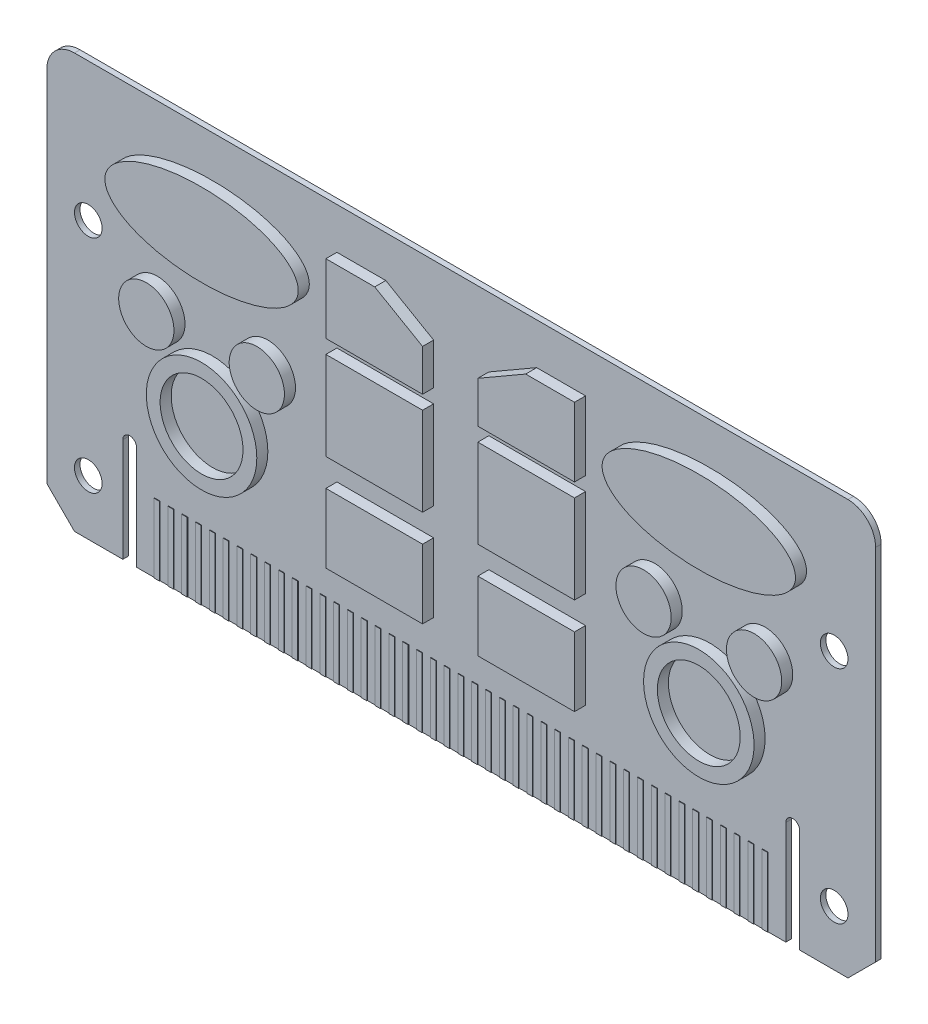
SolidWorks part; units mm, degrees
ref_plane "Front Plane" through (0, 0, 0) normal (0, 0, 1) x (1, 0, 0)
ref_plane "Top Plane" through (0, 0, 0) normal (0, 1, 0) x (1, 0, 0)
ref_plane "Right Plane" through (0, 0, 0) normal (1, 0, 0) x (0, 0, -1)
sketch "Sketch1" plane through (0, 0, 0) normal (0, 0, 1) x (1, 0, 0)
  line L0 (-300, 150) -> (-300, 0)
  line L1 (-300, 0) -> (0, 0)
  line L2 (0, 0) -> (0, 150)
  line L3 (0, 150) -> (-300, 150)
  point P4 (0, 0)
  point P5 (0, 0)
  point P6 (-125.1878, -83.3597)
  point P7 (-117.2815, -83.3597)
  point P8 (29.0712, -106.5204)
  point P9 (-94.6638, 45.4314)
  dimension "D1" = 300
  dimension "D2" = 150
extrude "PCB Base" add sketch "Sketch1" along normal mid plane 2 contours L3 L0 L1 L2
sketch "Sketch2" plane through (0, 0, 1) normal (0, 0, 1) x (1, 0, 0)
  line L0 (-300, 0) -> (0, 0) construction
  line L1 (-300, 150) -> (-300, 0) construction
  line L2 (0, 0) -> (0, 150) construction
  line L7 (-195, 38) -> (-160, 38)
  line L8 (-195, 38) -> (-195, 63)
  line L13 (-195, 63) -> (-160, 63)
  line L14 (-160, 38) -> (-160, 63)
  line L15 (-195, 73) -> (-160, 73)
  line L16 (-195, 73) -> (-195, 105)
  line L17 (-195, 105) -> (-160, 105)
  line L18 (-160, 73) -> (-160, 105)
  line L19 (-195, 110) -> (-160, 110)
  line L20 (-195, 110) -> (-195, 135)
  line L21 (-195, 135) -> (-177.3205, 135)
  line L22 (-160, 110) -> (-160, 125)
  line L23 (-160, 125) -> (-177.3205, 135)
  line L24 (-150, 150) -> (-150, 0) construction
  line L25 (0, 150) -> (-300, 150) construction
  line L26 (-140, 125) -> (-122.6795, 135)
  line L27 (-140, 110) -> (-140, 125)
  line L28 (-105, 135) -> (-122.6795, 135)
  line L29 (-105, 110) -> (-105, 135)
  line L30 (-105, 110) -> (-140, 110)
  line L31 (-140, 73) -> (-140, 105)
  line L32 (-105, 105) -> (-140, 105)
  line L33 (-105, 73) -> (-105, 105)
  line L34 (-105, 73) -> (-140, 73)
  line L35 (-140, 38) -> (-140, 63)
  line L36 (-105, 63) -> (-140, 63)
  line L37 (-105, 38) -> (-105, 63)
  line L38 (-105, 38) -> (-140, 38)
  circle A0 centre (-260, 85) radius 10
  circle A1 centre (-220, 85) radius 10
  circle A2 centre (-240, 60) radius 15
  circle A3 centre (-240, 60) radius 20
  circle A4 centre (-60, 60) radius 20
  circle A5 centre (-60, 60) radius 15
  circle A6 centre (-80, 85) radius 10
  circle A7 centre (-40, 85) radius 10
  ellipse E0 centre (-240, 120) end of major axis (-275, 120) minor radius 15
  ellipse E1 centre (-60, 120) end of major axis (-25, 120) minor radius 15
  dimension "D1" = 20
  dimension "D5" = 30
  dimension "D8" = 5
  dimension "D2" = 85
  dimension "D3" = 40
  dimension "D4" = 40
  dimension "D6" = 60
  dimension "D7" = 60
  dimension "D9" = 60
  dimension "D10" = 120
  dimension "D11" = 70
  dimension "D12" = 30
  dimension "D13" = 38
  dimension "D14" = 73
  dimension "D15" = 25
  dimension "D16" = 32
  dimension "D17" = 110
  dimension "D18" = 135
  dimension "D19" = 160
  dimension "D20" = 195
  dimension "D21" = 125
  dimension "D22" = 120
extrude "Chips" add sketch "Sketch2" along normal blind 4
mirror "Mirror1" about plane through (0, 0, 0) normal (0, 0, 1) of "Chips"
sketch "Sketch3" plane through (0, 0, 1) normal (0, 0, 1) x (1, 0, 0)
  line L0 (-272.5, 37.5) -> (-272.5, 0)
  line L1 (-300, 0) -> (0, 0) construction
  line L2 (-272.5, 0) -> (-267.5, 0)
  line L3 (-267.5, 0) -> (-267.5, 37.5)
  line L4 (-300, 150) -> (-300, 0) construction
  line L5 (-30, 0) -> (-30, 37.5) construction
  line L6 (-32.5, 0) -> (-32.5, 37.5)
  line L7 (-27.5, 0) -> (-27.5, 37.5)
  line L8 (-150, 150) -> (-150, 0) construction
  line L9 (0, 150) -> (-300, 150) construction
  arc A0 (-272.5, 37.5) -> (-267.5, 37.5) centre (-270, 37.5) cw
  arc A1 (-32.5, 0) -> (-27.5, 0) centre (-30, 0) ccw
  arc A2 (-27.5, 37.5) -> (-32.5, 37.5) centre (-30, 37.5) ccw
  point P7 (-30, 18.75)
  point P10 (-270, 40)
  dimension "D4" = 2.5
  dimension "D1" = 40
  dimension "D2" = 27.5
  dimension "D3" = 5
extrude "Slot Cuts" cut sketch "Sketch3" against normal blind 10
hole_wizard "Ø10.0mm Dowel Hole1" positions "Sketch4" profile "Sketch5" hole size "Ø10.0" standard "ANSI Metric" end condition through all
sketch "Sketch4" plane through (0, 0, 1) normal (0, 0, 1) x (1, 0, 0)
  line L0 (-300, 0) -> (-272.5, 0) construction
  line L2 (-300, 150) -> (-300, 0) construction
  line L3 (-150, 150) -> (-150, 0) construction
  line L4 (0, 150) -> (-300, 150) construction
  line L5 (-267.5, 0) -> (-32.5, 0) construction
  point P0 (-285, 20)
  point P2 (-285, 100)
  point P4 (-15, 100)
  point P6 (-15, 20)
  point P35 (0, 0)
  point P36 (0, 0)
  point P37 (0, 0)
  dimension "D1" = 20
  dimension "D2" = 15
  dimension "D3" = 100
sketch "Sketch5" plane through (-285, 20, 1) normal (1, 0, 0) x (0, -1, 0)
  line L0 (0, 0) -> (0, 6)
  line L1 (0, 6) -> (5, 6)
  line L2 (5, 6) -> (5, 0)
  line L5 (5, 0) -> (0, 0)
  line L11 (0, -6.35) -> (0, 107.95) construction
  dimension "Thru Hole Dia." = 10
  dimension "Thru Hole Depth" = 6
sketch "Sketch6" plane through (0, 0, 1) normal (0, 0, 1) x (1, 0, 0)
  line L0 (-267.5, 0) -> (-32.5, 0) construction
  line L1 (-261, 0) -> (-259, 0)
  line L2 (-261, 0) -> (-261, 25)
  line L3 (-261, 25) -> (-259, 25)
  line L4 (-259, 0) -> (-259, 25)
  line L5 (-267.5, 0) -> (-267.5, 37.5) construction
  dimension "D1" = 25
  dimension "D2" = 2
  dimension "D3" = 6.5
extrude "Contacts" add sketch "Sketch6" along normal blind 0.2
pattern_linear "LPattern1" count 45 spacing 5 along (1, 0, 0) of "Contacts"
fillet "Fillet2" radius 10 2 edges at (0, 150, 0) (-300, 150, 0)
chamfer "Chamfer2" distance 10 angle 45 2 edges at (0, 0, 0) (-300, 0, 0)
